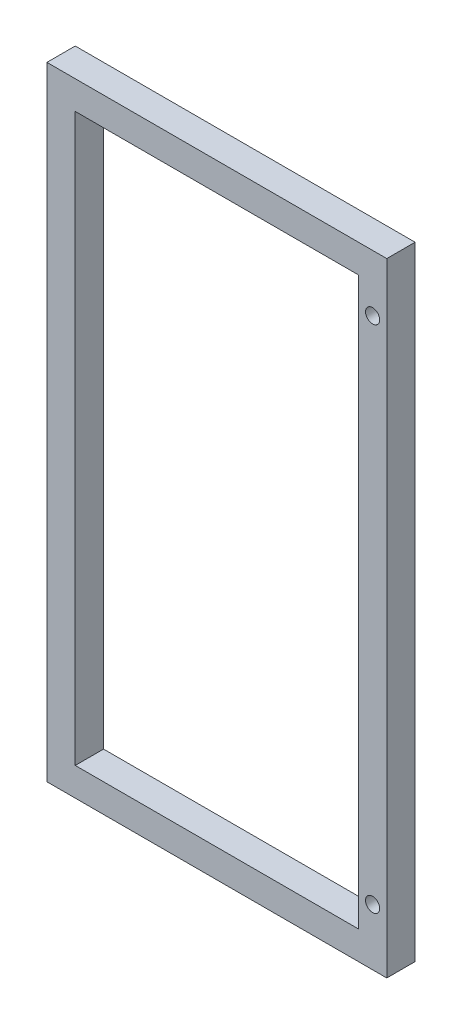
SolidWorks part; units mm, degrees
ref_plane "Front Plane" through (0, 0, 0) normal (0, 0, 1) x (1, 0, 0)
ref_plane "Top Plane" through (0, 0, 0) normal (0, 1, 0) x (1, 0, 0)
ref_plane "Right Plane" through (0, 0, 0) normal (1, 0, 0) x (0, 0, -1)
sketch "Sketch1" plane through (0, 0, 0) normal (0, 0, 1) x (1, 0, 0)
  line L1 (0, 0) -> (1000, 0)
  line L2 (0, 0) -> (0, 2000)
  line L3 (0, 2000) -> (1000, 2000)
  line L4 (1000, 0) -> (1000, 2000)
  line L5 (-100, -100) -> (1100, -100)
  line L6 (-100, -100) -> (-100, 2100)
  line L7 (-100, 2100) -> (1100, 2100)
  line L8 (1100, -100) -> (1100, 2100)
  dimension "D1" = 1000
  dimension "D2" = 2000
  dimension "D3" = 100
  dimension "D4" = 100
  dimension "D5" = 100
  dimension "D6" = 100
extrude "Boss-Extrude1" add sketch "Sketch1" along normal blind 100 contours L3 L4 L1 L2 | L7 L8 L5 L6
sketch "Sketch2" plane through (0, 0, 100) normal (0, 0, 1) x (1, 0, 0)
  line L0 (0, 1000) -> (1000, 1000) construction
  line L1 (0, 0) -> (0, 2000) construction
  line L2 (1000, 0) -> (1000, 2000) construction
  line L3 (1050, 1900) -> (1050, 100) construction
  line L4 (1000, 1000) -> (1100, 1000) construction
  line L5 (1100, -100) -> (1100, 2100) construction
  line L6 (0, 2000) -> (1000, 2000) construction
  circle A0 centre (1050, 1900) radius 25
  circle A1 centre (1050, 100) radius 25
  point P10 (1050, 1000)
  point P11 (0, 0)
  point P12 (1050, 1000)
  point P16 (1050, 1382.9742)
  point P19 (0, 0)
  dimension "D2" = 50
  dimension "D3" = 50
  dimension "D1" = 100
extrude "Cut-Extrude1" cut sketch "Sketch2" against normal through all
